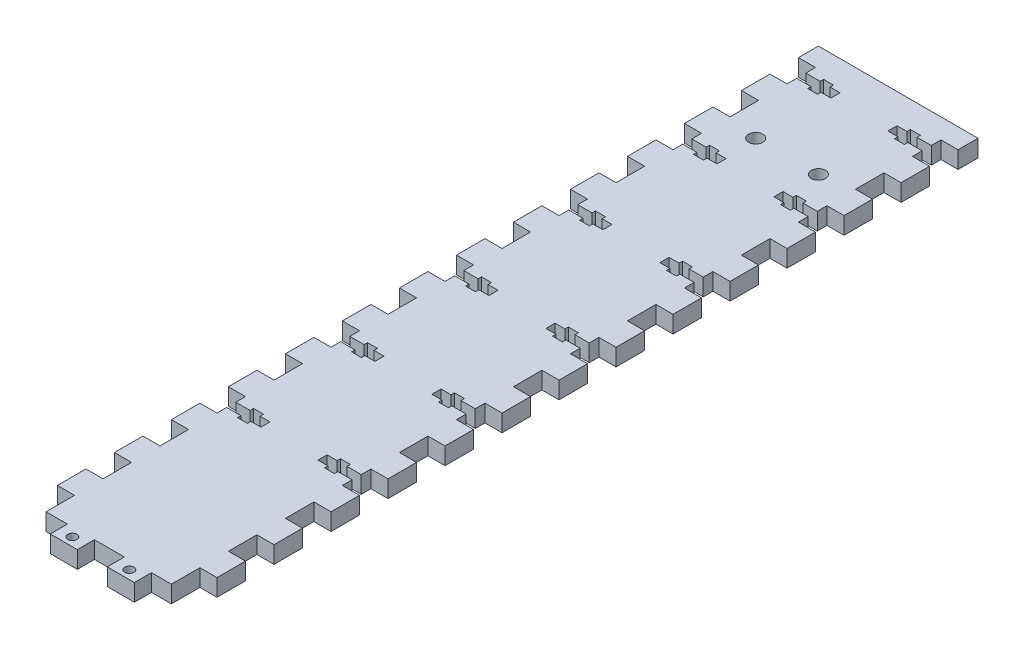
SolidWorks part; units mm, degrees
ref_plane "Plan de face" through (0, 0, 0) normal (0, 0, 1) x (1, 0, 0)
ref_plane "Plan de dessus" through (0, 0, 0) normal (0, 1, 0) x (1, 0, 0)
ref_plane "Plan de droite" through (0, 0, 0) normal (1, 0, 0) x (0, 0, -1)
sketch "Sketch1" plane through (0, 0, 0) normal (0, 0, 1) x (1, 0, 0)
  line L1 (-85.7436, 30.1282) -> (-29.7436, 30.1282)
  line L2 (-85.7436, 30.1282) -> (-85.7436, 24.1282)
  line L3 (-85.7436, 24.1282) -> (-29.7436, 24.1282)
  line L4 (-29.7436, 30.1282) -> (-29.7436, 24.1282)
  dimension "D1" = 56
  dimension "D2" = 6
extrude "Boss-Extrude1" add sketch "Sketch1" along normal blind 277
sketch "Sketch3" plane through (0, 30.1282, 0) normal (0, 1, 0) x (1, 0, 0)
  line L0 (-85.7436, -277) -> (-79.7436, -277)
  line L1 (-29.7436, -277) -> (-85.7436, -277) construction
  line L2 (-29.7436, 0) -> (-85.7436, 0) construction
  line L3 (-57.7436, 0) -> (-57.7436, -277) construction
  line L4 (-29.7436, -277) -> (-35.7436, -277)
  line L5 (-29.7436, -277) -> (-29.7436, -267)
  line L6 (-29.7436, -267) -> (-35.7436, -267)
  line L7 (-35.7436, -277) -> (-35.7436, -267)
  line L8 (-85.7436, -277) -> (-85.7436, -267)
  line L9 (-85.7436, -267) -> (-79.7436, -267)
  line L10 (-79.7436, -277) -> (-79.7436, -267)
  line L11 (-85.7436, -257) -> (-79.7436, -257)
  line L12 (-79.7436, -257) -> (-79.7436, -247)
  line L13 (-85.7436, -247) -> (-79.7436, -247)
  line L14 (-85.7436, -257) -> (-85.7436, -247)
  line L15 (-29.7436, -257) -> (-29.7436, -247)
  line L16 (-29.7436, -257) -> (-35.7436, -257)
  line L17 (-35.7436, -257) -> (-35.7436, -247)
  line L18 (-29.7436, -247) -> (-35.7436, -247)
  line L19 (-85.7436, -237) -> (-79.7436, -237)
  line L20 (-79.7436, -237) -> (-79.7436, -227)
  line L21 (-85.7436, -227) -> (-79.7436, -227)
  line L22 (-85.7436, -237) -> (-85.7436, -227)
  line L23 (-29.7436, -237) -> (-29.7436, -227)
  line L24 (-29.7436, -237) -> (-35.7436, -237)
  line L25 (-35.7436, -237) -> (-35.7436, -227)
  line L26 (-29.7436, -227) -> (-35.7436, -227)
  line L27 (-85.7436, -217) -> (-79.7436, -217)
  line L28 (-79.7436, -217) -> (-79.7436, -207)
  line L29 (-85.7436, -207) -> (-79.7436, -207)
  line L30 (-85.7436, -217) -> (-85.7436, -207)
  line L31 (-29.7436, -217) -> (-29.7436, -207)
  line L32 (-29.7436, -217) -> (-35.7436, -217)
  line L33 (-35.7436, -217) -> (-35.7436, -207)
  line L34 (-29.7436, -207) -> (-35.7436, -207)
  line L35 (-85.7436, -197) -> (-79.7436, -197)
  line L36 (-79.7436, -197) -> (-79.7436, -187)
  line L37 (-85.7436, -187) -> (-79.7436, -187)
  line L38 (-85.7436, -197) -> (-85.7436, -187)
  line L39 (-29.7436, -197) -> (-29.7436, -187)
  line L40 (-29.7436, -197) -> (-35.7436, -197)
  line L41 (-35.7436, -197) -> (-35.7436, -187)
  line L42 (-29.7436, -187) -> (-35.7436, -187)
  line L43 (-85.7436, -177) -> (-79.7436, -177)
  line L44 (-79.7436, -177) -> (-79.7436, -167)
  line L45 (-85.7436, -167) -> (-79.7436, -167)
  line L46 (-85.7436, -177) -> (-85.7436, -167)
  line L47 (-29.7436, -177) -> (-29.7436, -167)
  line L48 (-29.7436, -177) -> (-35.7436, -177)
  line L49 (-35.7436, -177) -> (-35.7436, -167)
  line L50 (-29.7436, -167) -> (-35.7436, -167)
  line L51 (-85.7436, -157) -> (-79.7436, -157)
  line L52 (-79.7436, -157) -> (-79.7436, -147)
  line L53 (-85.7436, -147) -> (-79.7436, -147)
  line L54 (-85.7436, -157) -> (-85.7436, -147)
  line L55 (-29.7436, -157) -> (-29.7436, -147)
  line L56 (-29.7436, -157) -> (-35.7436, -157)
  line L57 (-35.7436, -157) -> (-35.7436, -147)
  line L58 (-29.7436, -147) -> (-35.7436, -147)
  line L59 (-85.7436, -137) -> (-79.7436, -137)
  line L60 (-79.7436, -137) -> (-79.7436, -127)
  line L61 (-85.7436, -127) -> (-79.7436, -127)
  line L62 (-85.7436, -137) -> (-85.7436, -127)
  line L63 (-29.7436, -137) -> (-29.7436, -127)
  line L64 (-29.7436, -137) -> (-35.7436, -137)
  line L65 (-35.7436, -137) -> (-35.7436, -127)
  line L66 (-29.7436, -127) -> (-35.7436, -127)
  line L67 (-85.7436, -117) -> (-79.7436, -117)
  line L68 (-79.7436, -117) -> (-79.7436, -107)
  line L69 (-85.7436, -107) -> (-79.7436, -107)
  line L70 (-85.7436, -117) -> (-85.7436, -107)
  line L71 (-29.7436, -117) -> (-29.7436, -107)
  line L72 (-29.7436, -117) -> (-35.7436, -117)
  line L73 (-35.7436, -117) -> (-35.7436, -107)
  line L74 (-29.7436, -107) -> (-35.7436, -107)
  line L75 (-85.7436, -97) -> (-79.7436, -97)
  line L76 (-79.7436, -97) -> (-79.7436, -87)
  line L77 (-85.7436, -87) -> (-79.7436, -87)
  line L78 (-85.7436, -97) -> (-85.7436, -87)
  line L79 (-29.7436, -97) -> (-29.7436, -87)
  line L80 (-29.7436, -97) -> (-35.7436, -97)
  line L81 (-35.7436, -97) -> (-35.7436, -87)
  line L82 (-29.7436, -87) -> (-35.7436, -87)
  line L83 (-85.7436, -77) -> (-79.7436, -77)
  line L84 (-79.7436, -77) -> (-79.7436, -67)
  line L85 (-85.7436, -67) -> (-79.7436, -67)
  line L86 (-85.7436, -77) -> (-85.7436, -67)
  line L87 (-29.7436, -77) -> (-29.7436, -67)
  line L88 (-29.7436, -77) -> (-35.7436, -77)
  line L89 (-35.7436, -77) -> (-35.7436, -67)
  line L90 (-29.7436, -67) -> (-35.7436, -67)
  line L91 (-85.7436, -57) -> (-79.7436, -57)
  line L92 (-79.7436, -57) -> (-79.7436, -47)
  line L93 (-85.7436, -47) -> (-79.7436, -47)
  line L94 (-85.7436, -57) -> (-85.7436, -47)
  line L95 (-29.7436, -57) -> (-29.7436, -47)
  line L96 (-29.7436, -57) -> (-35.7436, -57)
  line L97 (-35.7436, -57) -> (-35.7436, -47)
  line L98 (-29.7436, -47) -> (-35.7436, -47)
  line L99 (-85.7436, -37) -> (-79.7436, -37)
  line L100 (-79.7436, -37) -> (-79.7436, -27)
  line L101 (-85.7436, -27) -> (-79.7436, -27)
  line L102 (-85.7436, -37) -> (-85.7436, -27)
  line L103 (-29.7436, -37) -> (-29.7436, -27)
  line L104 (-29.7436, -37) -> (-35.7436, -37)
  line L105 (-35.7436, -37) -> (-35.7436, -27)
  line L106 (-29.7436, -27) -> (-35.7436, -27)
  line L107 (-85.7436, -17) -> (-79.7436, -17)
  line L108 (-79.7436, -17) -> (-79.7436, -7)
  line L109 (-85.7436, -7) -> (-79.7436, -7)
  line L110 (-85.7436, -17) -> (-85.7436, -7)
  line L111 (-29.7436, -17) -> (-29.7436, -7)
  line L112 (-29.7436, -17) -> (-35.7436, -17)
  line L113 (-35.7436, -17) -> (-35.7436, -7)
  line L114 (-29.7436, -7) -> (-35.7436, -7)
  dimension "D1" = 6
  dimension "D2" = 10
  dimension "D3" = 14
extrude "Cut-Extrude1" cut sketch "Sketch3" against normal through all
sketch "Sketch6" plane through (0, 0, 277) normal (0, 0, 1) x (1, 0, 0)
  line L0 (-35.7436, 30.1282) -> (-79.7436, 30.1282) construction
  line L1 (-72.2436, 30.1282) -> (-62.7436, 30.1282)
  line L2 (-72.2436, 30.1282) -> (-72.2436, 24.1282)
  line L3 (-72.2436, 24.1282) -> (-62.7436, 24.1282)
  line L4 (-62.7436, 30.1282) -> (-62.7436, 24.1282)
  line L5 (-79.7436, 24.1282) -> (-35.7436, 24.1282) construction
  line L6 (-79.7436, 24.1282) -> (-79.7436, 30.1282) construction
  line L7 (-52.2436, 30.1282) -> (-52.2436, 24.1282)
  line L8 (-52.2436, 30.1282) -> (-42.7436, 30.1282)
  line L9 (-42.7436, 30.1282) -> (-42.7436, 24.1282)
  line L10 (-52.2436, 24.1282) -> (-42.7436, 24.1282)
  dimension "D1" = 7.5
  dimension "D2" = 9.5
  dimension "D3" = 2
extrude "Boss-Extrude2" add sketch "Sketch6" along normal blind 6
sketch "Sketch9" plane through (-35.7436, 0, 0) normal (1, 0, 0) x (0, 0, -1)
  line L0 (-257, 24.1282) -> (-247, 30.1282) construction
  line L1 (-247, 24.1282) -> (-257, 24.1282) construction
  line L2 (-250.4, 30.1282) -> (-253.6, 30.1282)
  line L3 (-250.4, 30.1282) -> (-250.4, 24.1282)
  line L4 (-250.4, 24.1282) -> (-253.6, 24.1282)
  line L5 (-253.6, 30.1282) -> (-253.6, 24.1282)
  line L6 (-250.4, 30.1282) -> (-253.6, 24.1282) construction
  line L7 (-250.4, 24.1282) -> (-253.6, 30.1282) construction
  line L8 (-210.4, 30.1282) -> (-210.4, 24.1282)
  line L9 (-210.4, 30.1282) -> (-213.6, 30.1282)
  line L10 (-213.6, 30.1282) -> (-213.6, 24.1282)
  line L11 (-210.4, 24.1282) -> (-213.6, 24.1282)
  line L12 (-170.4, 30.1282) -> (-170.4, 24.1282)
  line L13 (-170.4, 30.1282) -> (-173.6, 30.1282)
  line L14 (-173.6, 30.1282) -> (-173.6, 24.1282)
  line L15 (-170.4, 24.1282) -> (-173.6, 24.1282)
  line L16 (-130.4, 30.1282) -> (-130.4, 24.1282)
  line L17 (-130.4, 30.1282) -> (-133.6, 30.1282)
  line L18 (-133.6, 30.1282) -> (-133.6, 24.1282)
  line L19 (-130.4, 24.1282) -> (-133.6, 24.1282)
  line L20 (-90.4, 30.1282) -> (-90.4, 24.1282)
  line L21 (-90.4, 30.1282) -> (-93.6, 30.1282)
  line L22 (-93.6, 30.1282) -> (-93.6, 24.1282)
  line L23 (-90.4, 24.1282) -> (-93.6, 24.1282)
  line L24 (-50.4, 30.1282) -> (-50.4, 24.1282)
  line L25 (-50.4, 30.1282) -> (-53.6, 30.1282)
  line L26 (-53.6, 30.1282) -> (-53.6, 24.1282)
  line L27 (-50.4, 24.1282) -> (-53.6, 24.1282)
  line L28 (-10.4, 30.1282) -> (-10.4, 24.1282)
  line L29 (-10.4, 30.1282) -> (-13.6, 30.1282)
  line L30 (-13.6, 30.1282) -> (-13.6, 24.1282)
  line L31 (-10.4, 24.1282) -> (-13.6, 24.1282)
  point P4 (-252, 27.1282)
  dimension "D1" = 3.2
  dimension "D2" = 7
extrude "Cut-Extrude2" cut sketch "Sketch9" against normal blind 12
sketch "Sketch10" plane through (-79.7436, 0, 0) normal (-1, 0, 0) x (0, 0, 1)
  line L0 (257, 30.1282) -> (247, 24.1282) construction
  line L1 (257, 30.1282) -> (247, 30.1282) construction
  line L2 (250.4, 24.1282) -> (253.6, 24.1282)
  line L3 (250.4, 24.1282) -> (250.4, 30.1282)
  line L4 (250.4, 30.1282) -> (253.6, 30.1282)
  line L5 (253.6, 24.1282) -> (253.6, 30.1282)
  line L6 (250.4, 24.1282) -> (253.6, 30.1282) construction
  line L7 (250.4, 30.1282) -> (253.6, 24.1282) construction
  line L8 (210.4, 24.1282) -> (210.4, 30.1282)
  line L9 (210.4, 24.1282) -> (213.6, 24.1282)
  line L10 (213.6, 24.1282) -> (213.6, 30.1282)
  line L11 (210.4, 30.1282) -> (213.6, 30.1282)
  line L12 (170.4, 24.1282) -> (170.4, 30.1282)
  line L13 (170.4, 24.1282) -> (173.6, 24.1282)
  line L14 (173.6, 24.1282) -> (173.6, 30.1282)
  line L15 (170.4, 30.1282) -> (173.6, 30.1282)
  line L16 (130.4, 24.1282) -> (130.4, 30.1282)
  line L17 (130.4, 24.1282) -> (133.6, 24.1282)
  line L18 (133.6, 24.1282) -> (133.6, 30.1282)
  line L19 (130.4, 30.1282) -> (133.6, 30.1282)
  line L20 (90.4, 24.1282) -> (90.4, 30.1282)
  line L21 (90.4, 24.1282) -> (93.6, 24.1282)
  line L22 (93.6, 24.1282) -> (93.6, 30.1282)
  line L23 (90.4, 30.1282) -> (93.6, 30.1282)
  line L24 (50.4, 24.1282) -> (50.4, 30.1282)
  line L25 (50.4, 24.1282) -> (53.6, 24.1282)
  line L26 (53.6, 24.1282) -> (53.6, 30.1282)
  line L27 (50.4, 30.1282) -> (53.6, 30.1282)
  line L28 (10.4, 24.1282) -> (10.4, 30.1282)
  line L29 (10.4, 24.1282) -> (13.6, 24.1282)
  line L30 (13.6, 24.1282) -> (13.6, 30.1282)
  line L31 (10.4, 30.1282) -> (13.6, 30.1282)
  point P4 (252, 27.1282)
  dimension "D1" = 3.2
  dimension "D2" = 7
extrude "Cut-Extrude3" cut sketch "Sketch10" against normal blind 12
sketch "Sketch11" plane through (0, 24.1282, 0) normal (0, -1, 0) x (1, 0, 0)
  line L0 (-57.7436, 277) -> (-57.7436, 0) construction
  line L1 (-74.7436, 254.8) -> (-71.2436, 254.8)
  line L2 (-74.7436, 254.8) -> (-74.7436, 249.2)
  line L3 (-74.7436, 249.2) -> (-71.2436, 249.2)
  line L4 (-71.2436, 254.8) -> (-71.2436, 249.2)
  line L6 (-85.7436, 0) -> (-29.7436, 0) construction
  line L7 (-47.7436, 250.4) -> (-47.7436, 253.6) construction
  line L8 (-79.7436, 257) -> (-79.7436, 253.6) construction
  line L9 (-40.7436, 249.2) -> (-44.2436, 249.2)
  line L10 (-44.2436, 254.8) -> (-44.2436, 249.2)
  line L11 (-40.7436, 254.8) -> (-44.2436, 254.8)
  line L12 (-40.7436, 254.8) -> (-40.7436, 249.2)
  line L13 (-74.7436, 214.8) -> (-74.7436, 209.2)
  line L14 (-74.7436, 214.8) -> (-71.2436, 214.8)
  line L15 (-71.2436, 214.8) -> (-71.2436, 209.2)
  line L16 (-74.7436, 209.2) -> (-71.2436, 209.2)
  line L17 (-40.7436, 209.2) -> (-44.2436, 209.2)
  line L18 (-44.2436, 214.8) -> (-44.2436, 209.2)
  line L19 (-40.7436, 214.8) -> (-44.2436, 214.8)
  line L20 (-40.7436, 214.8) -> (-40.7436, 209.2)
  line L21 (-74.7436, 174.8) -> (-74.7436, 169.2)
  line L22 (-74.7436, 174.8) -> (-71.2436, 174.8)
  line L23 (-71.2436, 174.8) -> (-71.2436, 169.2)
  line L24 (-74.7436, 169.2) -> (-71.2436, 169.2)
  line L25 (-40.7436, 169.2) -> (-44.2436, 169.2)
  line L26 (-44.2436, 174.8) -> (-44.2436, 169.2)
  line L27 (-40.7436, 174.8) -> (-44.2436, 174.8)
  line L28 (-40.7436, 174.8) -> (-40.7436, 169.2)
  line L29 (-74.7436, 134.8) -> (-74.7436, 129.2)
  line L30 (-74.7436, 134.8) -> (-71.2436, 134.8)
  line L31 (-71.2436, 134.8) -> (-71.2436, 129.2)
  line L32 (-74.7436, 129.2) -> (-71.2436, 129.2)
  line L33 (-40.7436, 129.2) -> (-44.2436, 129.2)
  line L34 (-44.2436, 134.8) -> (-44.2436, 129.2)
  line L35 (-40.7436, 134.8) -> (-44.2436, 134.8)
  line L36 (-40.7436, 134.8) -> (-40.7436, 129.2)
  line L37 (-74.7436, 94.8) -> (-74.7436, 89.2)
  line L38 (-74.7436, 94.8) -> (-71.2436, 94.8)
  line L39 (-71.2436, 94.8) -> (-71.2436, 89.2)
  line L40 (-74.7436, 89.2) -> (-71.2436, 89.2)
  line L41 (-40.7436, 89.2) -> (-44.2436, 89.2)
  line L42 (-44.2436, 94.8) -> (-44.2436, 89.2)
  line L43 (-40.7436, 94.8) -> (-44.2436, 94.8)
  line L44 (-40.7436, 94.8) -> (-40.7436, 89.2)
  line L45 (-74.7436, 54.8) -> (-74.7436, 49.2)
  line L46 (-74.7436, 54.8) -> (-71.2436, 54.8)
  line L47 (-71.2436, 54.8) -> (-71.2436, 49.2)
  line L48 (-74.7436, 49.2) -> (-71.2436, 49.2)
  line L49 (-40.7436, 49.2) -> (-44.2436, 49.2)
  line L50 (-44.2436, 54.8) -> (-44.2436, 49.2)
  line L51 (-40.7436, 54.8) -> (-44.2436, 54.8)
  line L52 (-40.7436, 54.8) -> (-40.7436, 49.2)
  line L53 (-74.7436, 14.8) -> (-74.7436, 9.2)
  line L55 (-74.7436, 14.8) -> (-71.2436, 14.8)
  line L56 (-71.2436, 14.8) -> (-71.2436, 9.2)
  line L57 (-74.7436, 9.2) -> (-71.2436, 9.2)
  line L58 (-40.7436, 9.2) -> (-44.2436, 9.2)
  line L59 (-44.2436, 14.8) -> (-44.2436, 9.2)
  line L60 (-40.7436, 14.8) -> (-44.2436, 14.8)
  line L61 (-40.7436, 14.8) -> (-40.7436, 9.2)
  point P10 (-74.7436, 252)
  point P52 (-47.7436, 252)
  dimension "D1" = 5.6
  dimension "D3" = 5
  dimension "D4" = 3.5
  dimension "D5" = 7
extrude "Cut-Extrude4" cut sketch "Sketch11" against normal blind 12
sketch "Sketch12" plane through (0, 24.1282, 0) normal (0, -1, 0) x (1, 0, 0)
  line L2 (-52.2436, 283) -> (-52.2436, 277) construction
  line L3 (-42.7436, 283) -> (-52.2436, 283) construction
  line L4 (-62.7436, 283) -> (-72.2436, 283) construction
  circle A0 centre (-67.4936, 280) radius 1.6
  circle A1 centre (-47.4936, 280) radius 1.6
  point P2 (-52.2436, 280)
  point P5 (-47.4936, 283)
  point P12 (-67.4936, 283)
  dimension "D1" = 3.2
  dimension "D2" = 3.2
extrude "Cut-Extrude5" cut sketch "Sketch12" against normal blind 12
sketch "Sketch17" plane through (0, 30.1282, 0) normal (0, 1, 0) x (1, 0, 0)
  line L1 (-35.7436, -257) -> (-79.7436, -257)
  line L2 (-35.7436, -257) -> (-35.7436, -247)
  line L3 (-35.7436, -247) -> (-79.7436, -247)
  line L4 (-79.7436, -257) -> (-79.7436, -247)
extrude "Boss-Extrude5" add sketch "Sketch17" against normal through all
sketch "Sketch15" plane through (0, 24.1282, 0) normal (0, -1, 0) x (1, 0, 0)
  line L0 (-57.7436, 0) -> (-57.7436, 66.6112) construction
  line L1 (-85.7436, 0) -> (-29.7436, 0) construction
  circle A0 centre (-68.7436, 39) radius 2.5
  circle A1 centre (-46.7436, 39) radius 2.5
  point P9 (-57.7436, 0)
  dimension "D1" = 5
  dimension "D2" = 11
  dimension "D3" = 39
extrude "Cut-Extrude7" cut sketch "Sketch15" against normal through all
